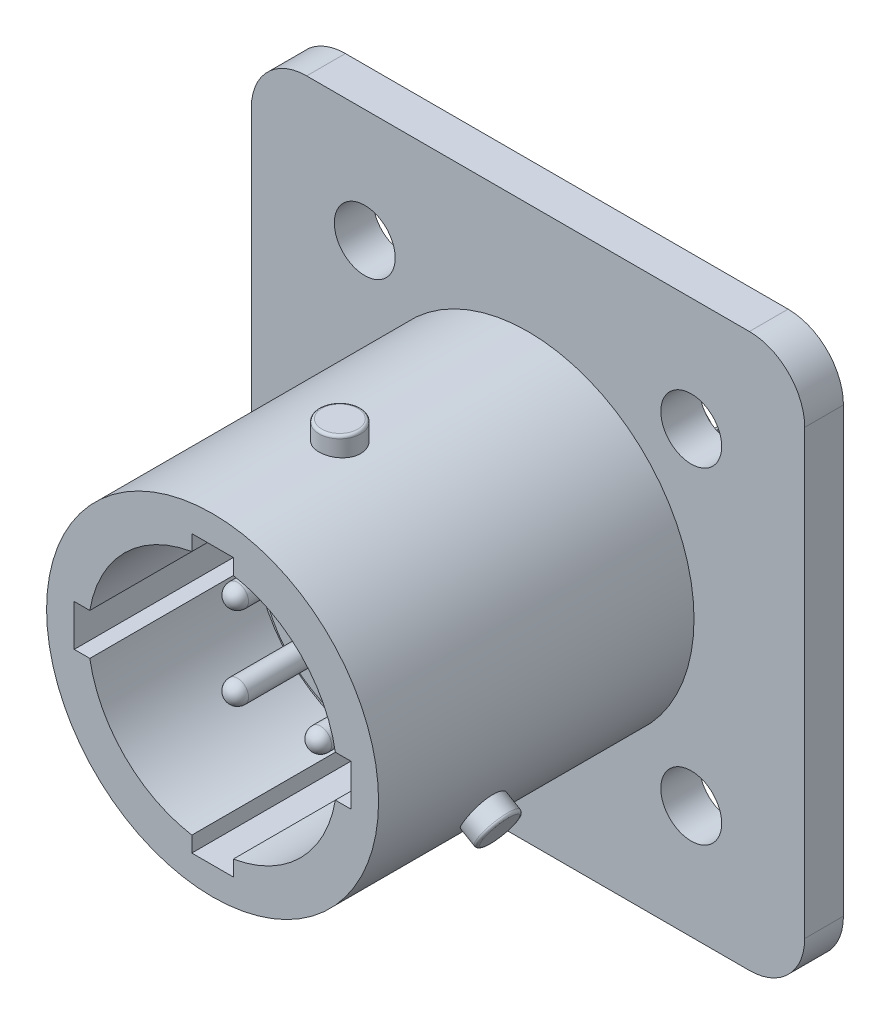
SolidWorks part; units mm, degrees
ref_plane "Спереди" through (0, 0, 0) normal (0, 0, 1) x (1, 0, 0)
ref_plane "Сверху" through (0, 0, 0) normal (0, 1, 0) x (1, 0, 0)
ref_plane "Справа" through (0, 0, 0) normal (1, 0, 0) x (0, 0, -1)
sketch "Эскиз1" plane through (0, 0, 0) normal (0, 0, 1) x (1, 0, 0)
  line L1 (-10, 10) -> (10, 10)
  line L2 (-10, 10) -> (-10, -10)
  line L3 (-10, -10) -> (10, -10)
  line L4 (10, 10) -> (10, -10)
  line L5 (0, -10) -> (0, 10) construction
  line L6 (-10, 0) -> (10, 0) construction
  point P0 (0, 0)
  dimension "D1" = 20
  dimension "D2" = 20
extrude "Бобышка-Вытянуть1" add sketch "Эскиз1" along normal mid plane 1.4
sketch "Эскиз2" plane through (0, 0, 0.7) normal (0, 0, 1) x (1, 0, 0)
  line L1 (-5.9, 5.9) -> (5.9, 5.9) construction
  line L2 (-5.9, 5.9) -> (-5.9, -5.9) construction
  line L3 (-5.9, -5.9) -> (5.9, -5.9) construction
  line L4 (5.9, 5.9) -> (5.9, -5.9) construction
  line L5 (0, -5.9) -> (0, 5.9) construction
  line L6 (-5.9, 0) -> (5.9, 0) construction
  circle A0 centre (-5.9, 5.9) radius 1.1
  circle A1 centre (5.9, 5.9) radius 1.1
  circle A2 centre (5.9, -5.9) radius 1.1
  circle A3 centre (-5.9, -5.9) radius 1.1
  point P0 (0, 0)
  dimension "D3" = 2.2
  dimension "D1" = 11.8
  dimension "D2" = 11.8
extrude "Вырез-Вытянуть1" cut sketch "Эскиз2" against normal blind 3.4
sketch "Эскиз4" plane through (0, 0, -0.7) normal (0, 0, -1) x (-1, 0, 0)
  circle A0 centre (0, 0) radius 5
  dimension "D1" = 10
extrude "Бобышка-Вытянуть2" add sketch "Эскиз4" along normal blind 1.6
sketch "Эскиз5" plane through (0, 0, 0.7) normal (0, 0, 1) x (1, 0, 0)
  circle A0 centre (0, 0) radius 6
  dimension "D1" = 12
extrude "Бобышка-Вытянуть3" add sketch "Эскиз5" along normal blind 11.4
sketch "Эскиз6" plane through (0, 0, -2.3) normal (0, 0, -1) x (-1, 0, 0)
  line L0 (-3.0222, 0) -> (2.9653, 0) construction
  line L1 (0, 2.9379) -> (0, -2.6139) construction
  circle A1 centre (-1.5, 1.5) radius 0.5
  circle A2 centre (0, 0) radius 4
  circle A3 centre (0, 0) radius 4
  circle A4 centre (1.5, 1.5) radius 0.5
  circle A5 centre (1.5, -1.5) radius 0.5
  circle A6 centre (-1.5, -1.5) radius 0.5
  point P12 (0, 1.4838)
  dimension "D2" = 1
  dimension "D3" = 1.5
  dimension "D4" = 1.5
  dimension "D1" = 1
extrude "Вырез-Вытянуть2" cut sketch "Эскиз6" against normal up to surface (1.6 mm away) up to face at (5, 0, -0.7)
sketch "Эскиз7" plane through (0, 0, -2.3) normal (0, 0, -1) x (-1, 0, 0)
  circle A0 centre (-1.5, 1.5) radius 0.5
  circle A2 centre (-1.5, -1.5) radius 0.5
  circle A3 centre (1.5, -1.5) radius 0.5
  circle A4 centre (1.5, 1.5) radius 0.5
extrude "Бобышка-Вытянуть4" add sketch "Эскиз7" along normal blind 2
sketch "Эскиз8" plane through (0, 0, 0) normal (1, 0, 0) x (0, 0, -1)
  line L0 (4.3, 2) -> (2.8726, 2)
  line L1 (4.3, 2) -> (0.7, 2) construction
  line L2 (4.3, 1) -> (4.3, 2) construction
  line L3 (4.3, -1) -> (2.8726, -1)
  line L4 (4.3, 2) -> (4.3, 1.5)
  line L5 (4.3, -1) -> (4.3, -1.5)
  arc A0 (2.8726, 2) -> (4.3, 1.5) centre (4.1984, 3.4974) ccw
  arc A1 (2.8726, -1) -> (4.3, -1.5) centre (4.1984, 0.4974) ccw
  dimension "D1" = 2
extrude "Вырез-Вытянуть3" cut sketch "Эскиз8" against normal mid plane 12
fillet "Скругление1" radius 2 4 edges at (-10, -10, 0) (10, -10, 0) (-10, 10, 0) (10, 10, 0)
sketch "Эскиз10" plane through (0, 0, -4.3) normal (0, 0, -1) x (-1, 0, 0)
  line L0 (1, 1.5) -> (2, 1.5) construction
  line L1 (-1, 1.5) -> (-2, 1.5) construction
  line L2 (-1, -1.5) -> (-2, -1.5) construction
  line L3 (1, -1.5) -> (2, -1.5) construction
  circle A0 centre (1.5, 1.5) radius 0.4
  circle A1 centre (-1.5, 1.5) radius 0.4
  circle A2 centre (-1.5, -1.5) radius 0.4
  circle A3 centre (1.5, -1.5) radius 0.4
  dimension "D1" = 0.8
extrude "Вырез-Вытянуть4" cut sketch "Эскиз10" against normal blind 3
sketch "Эскиз11" plane through (0, 0, 12.1) normal (0, 0, 1) x (1, 0, 0)
  line L0 (0, 7.0707) -> (0, -7.5997) construction
  line L1 (-7.9185, 0) -> (8.5925, 0) construction
  line L2 (-0.75, 5) -> (0.75, 5)
  line L3 (-0.75, 5) -> (-0.75, 4.4371)
  line L4 (0.75, 5) -> (0.75, 4.4371)
  line L5 (5, 0.75) -> (4.4371, 0.75)
  line L6 (5, 0.75) -> (5, -0.75)
  line L7 (5, -0.75) -> (4.4371, -0.75)
  line L8 (0.75, -5) -> (0.75, -4.4371)
  line L9 (0.75, -5) -> (-0.75, -5)
  line L10 (-0.75, -5) -> (-0.75, -4.4371)
  line L11 (-5, -0.75) -> (-4.4371, -0.75)
  line L12 (-5, -0.75) -> (-5, 0.75)
  line L13 (-5, 0.75) -> (-4.4371, 0.75)
  arc A1 (-4.4371, -0.75) -> (-0.75, -4.4371) centre (0, 0) ccw
  circle A2 centre (0, 0) radius 4.5
  arc A3 (-0.75, 4.4371) -> (-4.4371, 0.75) centre (0, 0) ccw
  arc A4 (0.75, -4.4371) -> (4.4371, -0.75) centre (0, 0) ccw
  arc A5 (4.4371, 0.75) -> (0.75, 4.4371) centre (0, 0) ccw
  point P10 (0, 4.5)
  point P11 (0, 5)
  point P28 (0, 0)
  dimension "D2" = 0.5
  dimension "D3" = 1.5
  dimension "D1" = 1.5
  dimension "D4" = 4
extrude "Вырез-Вытянуть5" cut sketch "Эскиз11" against normal blind 6
sketch "Эскиз12" plane through (0, 0, 6.1) normal (0, 0, 1) x (1, 0, 0)
  circle A0 centre (0, 0) radius 3.75
  dimension "D1" = 7.5
extrude "Бобышка-Вытянуть5" add sketch "Эскиз12" along normal blind 0.5
sketch "Эскиз13" plane through (0, 0, 6.6) normal (0, 0, 1) x (1, 0, 0)
  circle A0 centre (1.5, 1.5) radius 0.4
  circle A1 centre (-1.5, 1.5) radius 0.4
  circle A2 centre (1.5, -1.5) radius 0.4
  circle A3 centre (-1.5, -1.5) radius 0.4
extrude "Бобышка-Вытянуть6" add sketch "Эскиз13" along normal blind 3.5
fillet "Скругление2" radius 0.4 4 edges at (1.9, -1.5, 10.1) (-1.1, -1.5, 10.1) (1.9, 1.5, 10.1) (-1.1, 1.5, 10.1)
ref_plane "Плоскость1" through (0, 0, 7.5) normal (0, 0, 1) x (1, 0, 0)
sketch "Эскиз14" plane through (0, 0, 7.5) normal (0, 0, 1) x (1, 0, 0)
  line L0 (0, 6.8264) -> (0, 3.1156) construction
  line L1 (0, 6.6686) -> (0.65, 6.6686)
  line L2 (0, 6.6686) -> (0, 5.8686)
  line L3 (0, 5.8686) -> (0.75, 5.8686)
  line L4 (0.75, 5.8686) -> (0.75, 6.5686)
  arc A0 (0.75, 6.5686) -> (0.65, 6.6686) centre (0.65, 6.5686) ccw
  point P4 (0, 0)
  point P5 (0, 6.7094)
  dimension "D3" = 0.1
  dimension "D1" = 0.75
  dimension "D2" = 0.8
revolve "Повернуть1" add sketch "Эскиз14" angle 360 about L0
pattern_circular "Круговой массив1" count 3 every 120 about axis through (0, 0, 0) along (0, 0, 1) of "Повернуть1"
